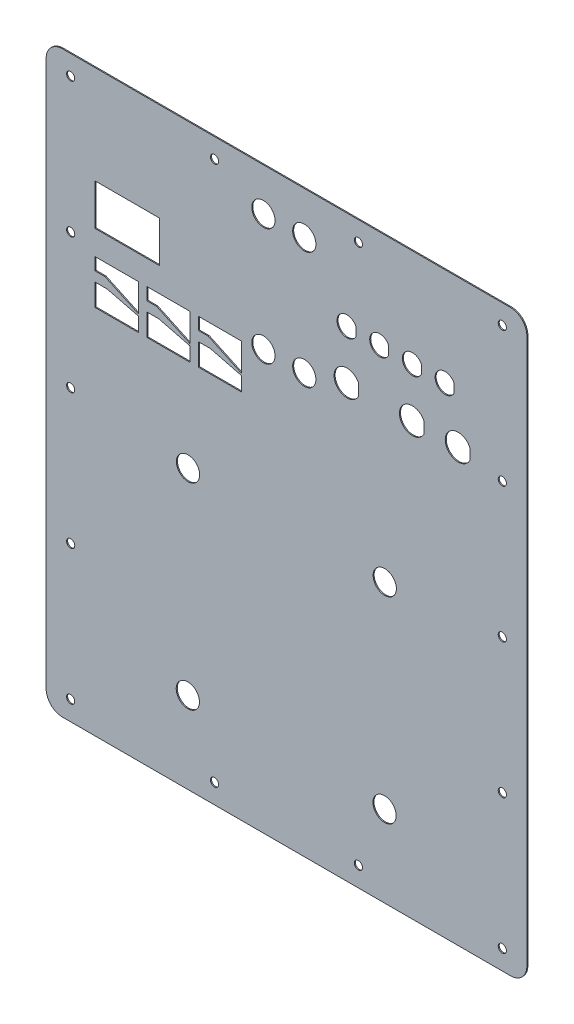
SolidWorks part; units mm, degrees
ref_plane "Front Plane" through (0, 0, 0) normal (0, 0, 1) x (1, 0, 0)
ref_plane "Top Plane" through (0, 0, 0) normal (0, 1, 0) x (1, 0, 0)
ref_plane "Right Plane" through (0, 0, 0) normal (1, 0, 0) x (0, 0, -1)
sketch "Sketch1" plane through (0, 0, 0) normal (0, 0, 1) x (1, 0, 0)
  line L0 (-98.4559, -29.8932) -> (-148.4431, -29.8932) construction
  line L1 (-98.4559, -61.8718) -> (-98.4559, -29.8932) construction
  line L2 (-148.4431, -61.8718) -> (-98.4559, -61.8718) construction
  line L3 (-148.4431, -80.8136) -> (-148.4431, -90.4058) construction
  line L4 (174.1369, 46.3068) -> (-173.8431, 46.3068)
  line L5 (-186.5431, 33.6068) -> (-186.5431, -390.5732)
  line L6 (-173.8431, -403.2732) -> (174.1369, -403.2732)
  line L7 (186.8369, -390.5732) -> (186.8369, 33.6068)
  line L8 (174.1369, 46.3068) -> (-173.8431, 46.3068)
  line L9 (-186.5431, 33.6068) -> (-186.5431, -390.5732)
  line L10 (-173.8431, -403.2732) -> (174.1369, -403.2732)
  line L11 (186.8369, -390.5732) -> (186.8369, 33.6068)
  line L12 (-148.4431, -29.8932) -> (-148.4431, -61.8718)
  line L14 (-98.4559, -61.8718) -> (-98.4559, -29.8932)
  line L16 (-148.4431, -29.8932) -> (-148.4431, -61.8718)
  line L18 (-98.4559, -61.8718) -> (-98.4559, -29.8932)
  line L20 (-114.8704, -80.8136) -> (-148.4431, -80.8136) construction
  line L30 (-114.8704, -115.0404) -> (-114.8704, -104.0311)
  line L31 (-148.4431, -97.927) -> (-148.4431, -115.0404)
  line L32 (-114.8704, -115.0404) -> (-114.8704, -104.0311)
  line L35 (-148.4431, -115.0404) -> (-114.8704, -115.0404)
  line L36 (-148.4431, -97.927) -> (-148.4431, -115.0404)
  line L37 (-68.2807, -90.4058) -> (-60.6506, -90.4058)
  line L40 (-148.4431, -115.0404) -> (-114.8704, -115.0404)
  line L43 (-68.2807, -90.4058) -> (-60.6506, -90.4058)
  line L44 (-74.7892, -115.0404) -> (-74.7892, -104.0311)
  line L45 (-108.3619, -115.0404) -> (-74.7892, -115.0404)
  line L48 (-68.2807, -80.8136) -> (-68.2807, -90.4058)
  line L49 (-74.7892, -115.0404) -> (-74.7892, -104.0311)
  line L50 (-108.3619, -115.0404) -> (-74.7892, -115.0404)
  line L51 (-74.7892, -102.5051) -> (-74.7892, -80.8136)
  line L52 (-100.7318, -90.4058) -> (-74.7892, -102.5051)
  line L53 (-68.2807, -80.8136) -> (-68.2807, -90.4058)
  line L54 (-34.708, -80.8136) -> (-68.2807, -80.8136)
  line L56 (-74.7892, -102.5051) -> (-74.7892, -80.8136)
  line L57 (-100.7318, -90.4058) -> (-74.7892, -102.5051)
  line L61 (-34.708, -102.5051) -> (-34.708, -80.8136)
  line L62 (-60.6506, -90.4058) -> (-34.708, -102.5051)
  line L63 (-34.708, -80.8136) -> (-68.2807, -80.8136)
  line L64 (-59.0155, -97.927) -> (-68.2807, -97.927)
  line L65 (-59.0155, -97.927) -> (-68.2807, -97.927)
  line L66 (-34.708, -102.5051) -> (-34.708, -80.8136)
  line L67 (-60.6506, -90.4058) -> (-34.708, -102.5051)
  line L68 (-34.708, -104.0311) -> (-59.0155, -97.927)
  line L69 (-34.708, -104.0311) -> (-59.0155, -97.927)
  line L70 (-108.3619, -97.927) -> (-108.3619, -115.0404)
  line L71 (-68.2807, -97.927) -> (-68.2807, -115.0404)
  line L72 (-108.3619, -97.927) -> (-108.3619, -115.0404)
  line L73 (-99.0967, -97.927) -> (-108.3619, -97.927)
  line L74 (-34.708, -115.0404) -> (-34.708, -104.0311)
  line L75 (-68.2807, -115.0404) -> (-34.708, -115.0404)
  line L76 (-68.2807, -97.927) -> (-68.2807, -115.0404)
  line L77 (-99.0967, -97.927) -> (-108.3619, -97.927)
  line L79 (-34.708, -115.0404) -> (-34.708, -104.0311)
  line L80 (-68.2807, -115.0404) -> (-34.708, -115.0404)
  line L81 (-114.8704, -102.5051) -> (-114.8704, -80.8136) construction
  line L82 (-140.813, -90.4058) -> (-114.8704, -102.5051) construction
  line L83 (-139.1779, -97.927) -> (-148.4431, -97.927) construction
  line L84 (-148.4431, -97.927) -> (-148.4431, -115.0404) construction
  line L85 (-148.4431, -115.0404) -> (-114.8704, -115.0404) construction
  line L86 (-114.8704, -115.0404) -> (-139.1779, -97.927) construction
  line L87 (-98.4559, -29.8932) -> (-148.4431, -29.8932)
  line L88 (-98.4559, -61.8718) -> (-98.4559, -29.8932)
  line L89 (-148.4431, -61.8718) -> (-98.4559, -61.8718)
  line L90 (-148.4431, -80.8136) -> (-148.4431, -90.4058)
  line L91 (-114.8704, -80.8136) -> (-148.4431, -80.8136)
  line L92 (-114.8704, -102.5051) -> (-114.8704, -80.8136)
  line L93 (-140.813, -90.4058) -> (-114.8704, -102.5051)
  line L94 (-139.1779, -97.927) -> (-148.4431, -97.927)
  line L95 (-148.4431, -97.927) -> (-148.4431, -115.0404)
  line L96 (-148.4431, -115.0404) -> (-114.8704, -115.0404)
  line L97 (-114.8704, -115.0404) -> (-139.1779, -97.927)
  line L98 (56.1539, -72.3926) -> (56.1539, -63.5937) construction
  line L99 (106.9539, -72.3926) -> (106.9539, -63.5937) construction
  line L100 (142.5139, -72.3926) -> (142.5139, -63.5937) construction
  line L101 (130.3727, -33.1356) -> (130.3727, -26.6507) construction
  line L102 (104.9727, -33.1356) -> (104.9727, -26.6507) construction
  line L103 (79.5727, -33.1356) -> (79.5727, -26.6507) construction
  line L104 (54.1727, -33.1356) -> (54.1727, -26.6507) construction
  line L105 (56.1539, -72.3926) -> (56.1539, -63.5937)
  line L106 (106.9539, -72.3926) -> (106.9539, -63.5937)
  line L107 (142.5139, -72.3926) -> (142.5139, -63.5937)
  line L108 (130.3727, -33.1356) -> (130.3727, -26.6507)
  line L109 (104.9727, -33.1356) -> (104.9727, -26.6507)
  line L110 (79.5727, -33.1356) -> (79.5727, -26.6507)
  line L111 (54.1727, -33.1356) -> (54.1727, -26.6507)
  line L271 (-98.4559, -29.8932) -> (-148.4431, -29.8932)
  line L272 (-98.4559, -29.8932) -> (-148.4431, -29.8932)
  line L279 (-148.4431, -61.8718) -> (-98.4559, -61.8718)
  line L280 (-148.4431, -61.8718) -> (-98.4559, -61.8718)
  line L289 (-139.1779, -97.927) -> (-148.4431, -97.927)
  line L290 (-139.1779, -97.927) -> (-148.4431, -97.927)
  line L316 (-114.8704, -102.5051) -> (-114.8704, -80.8136)
  line L317 (-114.8704, -102.5051) -> (-114.8704, -80.8136)
  line L322 (-140.813, -90.4058) -> (-114.8704, -102.5051)
  line L323 (-140.813, -90.4058) -> (-114.8704, -102.5051)
  line L365 (-74.7892, -104.0311) -> (-99.0967, -97.927)
  line L366 (-74.7892, -104.0311) -> (-99.0967, -97.927)
  line L487 (-148.4431, -90.4058) -> (-140.813, -90.4058)
  line L488 (-148.4431, -90.4058) -> (-140.813, -90.4058)
  line L489 (-148.4431, -80.8136) -> (-148.4431, -90.4058)
  line L490 (-148.4431, -80.8136) -> (-148.4431, -90.4058)
  line L493 (-114.8704, -80.8136) -> (-148.4431, -80.8136)
  line L494 (-114.8704, -80.8136) -> (-148.4431, -80.8136)
  line L521 (-114.8704, -104.0311) -> (-139.1779, -97.927)
  line L522 (-114.8704, -104.0311) -> (-139.1779, -97.927)
  line L525 (-108.3619, -90.4058) -> (-100.7318, -90.4058)
  line L526 (-108.3619, -90.4058) -> (-100.7318, -90.4058)
  line L527 (-108.3619, -80.8136) -> (-108.3619, -90.4058)
  line L528 (-108.3619, -80.8136) -> (-108.3619, -90.4058)
  line L529 (-74.7892, -80.8136) -> (-108.3619, -80.8136)
  line L530 (-74.7892, -80.8136) -> (-108.3619, -80.8136)
  circle A0 centre (-167.4931, -388.0332) radius 3.175 construction
  circle A1 centre (-167.4931, -283.2582) radius 3.175 construction
  circle A2 centre (-167.4931, -178.4832) radius 3.175 construction
  circle A3 centre (-167.4931, -73.7082) radius 3.175 construction
  arc A4 (186.8369, 33.6068) -> (174.1369, 46.3068) centre (174.1369, 33.6068) ccw
  arc A5 (-173.8431, 46.3068) -> (-186.5431, 33.6068) centre (-173.8431, 33.6068) ccw
  arc A6 (-186.5431, -390.5732) -> (-173.8431, -403.2732) centre (-173.8431, -390.5732) ccw
  arc A7 (174.1369, -403.2732) -> (186.8369, -390.5732) centre (174.1369, -390.5732) ccw
  arc A8 (186.8369, 33.6068) -> (174.1369, 46.3068) centre (174.1369, 33.6068) ccw
  arc A9 (-173.8431, 46.3068) -> (-186.5431, 33.6068) centre (-173.8431, 33.6068) ccw
  arc A10 (-186.5431, -390.5732) -> (-173.8431, -403.2732) centre (-173.8431, -390.5732) ccw
  arc A11 (174.1369, -403.2732) -> (186.8369, -390.5732) centre (174.1369, -390.5732) ccw
  circle A12 centre (-167.4931, 31.0668) radius 3.175 construction
  circle A13 centre (-55.7331, 31.0668) radius 3.175 construction
  circle A14 centre (56.0269, 31.0668) radius 3.175 construction
  circle A15 centre (167.7869, 31.0668) radius 3.175 construction
  circle A16 centre (167.7869, -73.7082) radius 3.175 construction
  circle A17 centre (167.7869, -178.4832) radius 3.175 construction
  circle A18 centre (167.7869, -283.2582) radius 3.175 construction
  circle A19 centre (167.7869, -388.0332) radius 3.175 construction
  circle A20 centre (56.0269, -388.0332) radius 3.175 construction
  circle A21 centre (-55.7331, -388.0332) radius 3.175 construction
  circle A22 centre (-167.4931, -388.0332) radius 3.175
  circle A23 centre (-167.4931, -283.2582) radius 3.175
  circle A24 centre (-167.4931, -178.4832) radius 3.175
  circle A25 centre (-167.4931, -73.7082) radius 3.175
  circle A26 centre (-167.4931, 31.0668) radius 3.175
  circle A27 centre (-55.7331, 31.0668) radius 3.175
  circle A28 centre (56.0269, 31.0668) radius 3.175
  circle A29 centre (167.7869, 31.0668) radius 3.175
  circle A30 centre (167.7869, -73.7082) radius 3.175
  circle A31 centre (167.7869, -178.4832) radius 3.175
  circle A32 centre (167.7869, -283.2582) radius 3.175
  circle A33 centre (167.7869, -388.0332) radius 3.175
  circle A34 centre (56.0269, -388.0332) radius 3.175
  circle A35 centre (-55.7331, -388.0332) radius 3.175
  circle A36 centre (-76.479, -339.9053) radius 9.0361
  circle A37 centre (-76.3322, -187.0941) radius 9.0361
  circle A38 centre (76.479, -187.241) radius 9.0361
  circle A39 centre (76.3322, -340.0522) radius 9.0361
  circle A40 centre (13.97, -77.7722) radius 9.036
  circle A41 centre (-17.78, -77.7722) radius 9.036
  circle A42 centre (-17.78, 13.2868) radius 9.0361
  circle A43 centre (13.97, 13.2868) radius 9.0361
  arc A44 (56.1539, -63.5937) -> (56.1539, -72.3926) centre (47.1369, -67.9932) ccw construction
  arc A45 (106.9539, -63.5937) -> (106.9539, -72.3926) centre (97.9369, -67.9932) ccw construction
  arc A46 (142.5139, -63.5937) -> (142.5139, -72.3926) centre (133.4969, -67.9932) ccw construction
  arc A47 (130.3727, -26.6507) -> (130.3727, -33.1356) centre (123.3369, -29.8932) ccw construction
  arc A48 (104.9727, -26.6507) -> (104.9727, -33.1356) centre (97.9369, -29.8932) ccw construction
  arc A49 (79.5727, -26.6507) -> (79.5727, -33.1356) centre (72.5369, -29.8932) ccw construction
  arc A50 (54.1727, -26.6507) -> (54.1727, -33.1356) centre (47.1369, -29.8932) ccw construction
  arc A51 (56.1539, -63.5937) -> (56.1539, -72.3926) centre (47.1369, -67.9932) ccw
  arc A52 (106.9539, -63.5937) -> (106.9539, -72.3926) centre (97.9369, -67.9932) ccw
  arc A53 (142.5139, -63.5937) -> (142.5139, -72.3926) centre (133.4969, -67.9932) ccw
  arc A54 (130.3727, -26.6507) -> (130.3727, -33.1356) centre (123.3369, -29.8932) ccw
  arc A55 (104.9727, -26.6507) -> (104.9727, -33.1356) centre (97.9369, -29.8932) ccw
  arc A56 (79.5727, -26.6507) -> (79.5727, -33.1356) centre (72.5369, -29.8932) ccw
  arc A57 (54.1727, -26.6507) -> (54.1727, -33.1356) centre (47.1369, -29.8932) ccw
  dimension "D9" = 18.0721
  dimension "D1" = 0
  dimension "D2" = 0
  dimension "D3" = 0
  dimension "D4" = 0
  dimension "D5" = 0
  dimension "D6" = 0
  dimension "D7" = 0
  dimension "D8" = 0
extrude "Boss-Extrude1" add sketch "Sketch1" along normal blind 0.7937 contours L10 A11 L11 A8 L8 A9 L9 A10 A57 L111 A56 L110 A55 L109 A54 L108 A53 L107 A52 L106 A51 L105 A43 A42 A41 A40 A39 A38 A37 A36 A35 A34 A33
